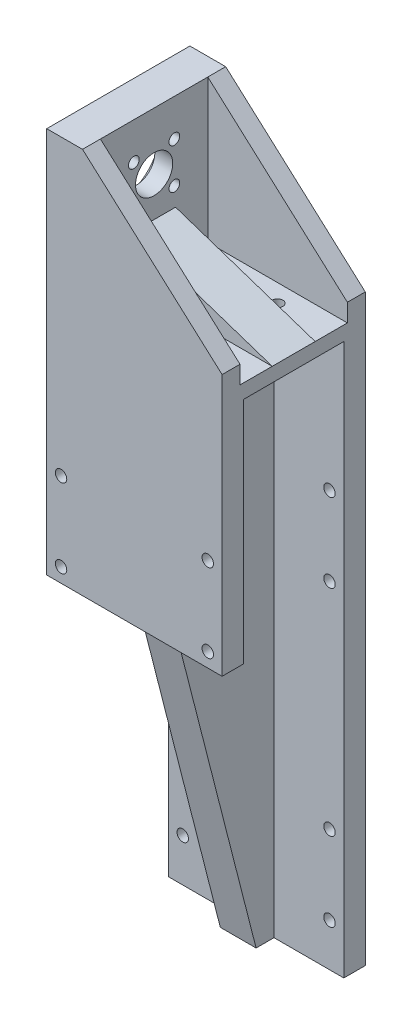
SolidWorks part; units mm, degrees
ref_plane "前视基准面" through (0, 0, 0) normal (0, 0, 1) x (1, 0, 0)
ref_plane "上视基准面" through (0, 0, 0) normal (0, 1, 0) x (1, 0, 0)
ref_plane "右视基准面" through (0, 0, 0) normal (1, 0, 0) x (0, 0, -1)
other "Configuration Table"
sketch "草图1" plane through (0, 0, 0) normal (0, 1, 0) x (1, 0, 0)
  line L1 (-24.5, -20) -> (24.5, -20)
  line L2 (-24.5, -20) -> (-24.5, 20)
  line L3 (-24.5, 20) -> (24.5, 20)
  line L4 (24.5, -20) -> (24.5, 20)
  line L5 (-24.5, -20) -> (24.5, 20) construction
  line L6 (-24.5, 20) -> (24.5, -20) construction
  point P0 (0, 0)
  dimension "D1" = 49
  dimension "D2" = 40
extrude "凸台-拉伸1" add sketch "草图1" along normal blind 4
sketch "草图2" plane through (0, 4, 0) normal (0, 1, 0) x (1, 0, 0)
  line L0 (0, 20) -> (0, -20) construction
  line L1 (24.5, 20) -> (-24.5, 20) construction
  line L2 (-24.5, -20) -> (24.5, -20) construction
  line L3 (-24.5, 0) -> (24.5, 0) construction
  line L4 (-24.5, 20) -> (-24.5, -20) construction
  line L5 (24.5, -20) -> (24.5, 20) construction
  circle A0 centre (-10, 10) radius 1.5
  circle A1 centre (10, 10) radius 1.5
  circle A2 centre (10, -10) radius 1.5
  circle A3 centre (-10, -10) radius 1.5
  dimension "D1" = 3
  dimension "D2" = 3
  dimension "D3" = 3
  dimension "D4" = 3
  dimension "D5" = 20
  dimension "D6" = 20
extrude "切除-拉伸1" cut sketch "草图2" against normal through all
sketch "草图3" plane through (0, 4, 0) normal (0, 1, 0) x (1, 0, 0)
  line L5 (-24.5, 0) -> (24.5, 0) construction
  line L6 (-24.5, 20) -> (-24.5, -20) construction
  line L7 (24.5, -20) -> (24.5, 20) construction
  line L9 (-24.5, 15) -> (-14.5, 15)
  line L10 (-24.5, 15) -> (-24.5, -15)
  line L11 (-24.5, -15) -> (-14.5, -15)
  line L12 (-14.5, 15) -> (-14.5, -15)
  dimension "D1" = 10
  dimension "D2" = 30
extrude "凸台-拉伸3" add sketch "草图3" along normal blind 40
sketch "草图4" plane through (-24.5, 0, 0) normal (-1, 0, 0) x (0, 0, 1)
  line L0 (0, 44) -> (0, 0) construction
  line L1 (-15, 44) -> (15, 44) construction
  line L2 (15, 4) -> (20, 4) construction
  circle A0 centre (0, 28) radius 5.2
  dimension "D1" = 10.4
  dimension "D2" = 24
extrude "切除-拉伸2" cut sketch "草图4" against normal through all
sketch "草图5" plane through (-24.5, 0, 0) normal (-1, 0, 0) x (0, 0, 1)
  circle A0 centre (0, 28) radius 11.75
  dimension "D1" = 23.5
extrude "切除-拉伸3" cut sketch "草图5" against normal blind 5
sketch "草图6" plane through (-19.5, 0, 0) normal (-1, 0, 0) x (0, 0, 1)
  line L1 (-5.6569, 22.3431) -> (5.6569, 22.3431) construction
  line L2 (-5.6569, 22.3431) -> (-5.6569, 33.6569) construction
  line L3 (-5.6569, 33.6569) -> (5.6569, 33.6569) construction
  line L4 (5.6569, 22.3431) -> (5.6569, 33.6569) construction
  line L5 (-5.6569, 22.3431) -> (5.6569, 33.6569) construction
  line L6 (-5.6569, 33.6569) -> (5.6569, 22.3431) construction
  circle A0 centre (0, 28) radius 8 construction
  circle A1 centre (-5.6569, 33.6569) radius 1.5
  circle A2 centre (5.6569, 33.6569) radius 1.5
  circle A3 centre (5.6569, 22.3431) radius 1.5
  circle A4 centre (-5.6569, 22.3431) radius 1.5
  dimension "D1" = 16
  dimension "D2" = 3
  dimension "D3" = 3
  dimension "D4" = 3
  dimension "D5" = 3
extrude "切除-拉伸4" cut sketch "草图6" against normal through all
ref_plane "基准面2" through (0, 0, 0) normal (0, 0, -1) x (-1, 0, 0)
sketch "草图7" plane through (0, 0, 0) normal (0, 0, -1) x (-1, 0, 0)
  line L0 (14.5, 17) -> (-24.5, 4)
  line L1 (14.5, 44) -> (14.5, 4) construction
  line L2 (-24.5, 4) -> (14.5, 4)
  line L3 (14.5, 4) -> (14.5, 17)
  dimension "D1" = 13
extrude "凸台-拉伸4" add sketch "草图7" along normal mid plane 12
sketch "草图8" plane through (-24.5, 0, 0) normal (-1, 0, 0) x (0, 0, 1)
  line L1 (20, 0) -> (14, 0)
  line L2 (20, 0) -> (20, -64)
  line L3 (20, -64) -> (14, -64)
  line L4 (14, 0) -> (14, -64)
  line L5 (-20, 0) -> (-14, 0)
  line L6 (-20, 0) -> (-20, -64)
  line L7 (-20, -64) -> (-14, -64)
  line L8 (-14, 0) -> (-14, -64)
  dimension "D1" = 6
  dimension "D2" = 6
  dimension "D3" = 64
  dimension "D4" = 64
extrude "凸台-拉伸5" add sketch "草图8" against normal up to surface (49 mm away) up to face at (24.5, 2.6667, 0)
sketch "草图9" plane through (0, 0, 20) normal (0, 0, 1) x (1, 0, 0)
  line L0 (24.5, 4) -> (24.5, -64) construction
  line L1 (24.5, -64) -> (-24.5, -64) construction
  line L2 (-24.5, 4) -> (-24.5, -64) construction
  circle A0 centre (20.5, -60) radius 1.6
  circle A1 centre (-20.5, -60) radius 1.6
  circle A2 centre (20.5, -38) radius 1.6
  circle A3 centre (-20.5, -38) radius 1.6
  dimension "D1" = 3.2
  dimension "D2" = 3.2
  dimension "D3" = 3.2
  dimension "D4" = 3.2
  dimension "D5" = 4
  dimension "D6" = 4
  dimension "D7" = 4
  dimension "D8" = 4
  dimension "D9" = 4
  dimension "D10" = 26
  dimension "D11" = 4
  dimension "D12" = 26
extrude "切除-拉伸5" cut sketch "草图9" against normal through all
sketch "草图11" plane through (0, 0, 15) normal (0, 0, 1) x (1, 0, 0)
  line L0 (-14.5, 44) -> (24.5, 9)
  line L1 (-24.5, 4) -> (-14.5, 4)
  line L2 (-24.5, 4) -> (-24.5, 44)
  line L3 (-24.5, 44) -> (-14.5, 44)
  line L5 (24.5, 9) -> (24.5, 4)
  line L6 (24.5, 4) -> (-14.5, 4)
  dimension "D1" = 5
extrude "凸台-拉伸6" add sketch "草图11" along normal blind 5
mirror "镜向2" about plane through (0, 0, 0) normal (0, 0, -1) of "凸台-拉伸6"
sketch "草图12" plane through (0, -64, 0) normal (0, -1, 0) x (1, 0, 0)
  line L1 (-24.5, -14) -> (24.5, -14)
  line L2 (-24.5, -14) -> (-24.5, -20)
  line L3 (-24.5, -20) -> (24.5, -20)
  line L4 (24.5, -14) -> (24.5, -20)
extrude "凸台-拉伸7" add sketch "草图12" along normal blind 90
sketch "草图13" plane through (0, 0, -20) normal (0, 0, -1) x (-1, 0, 0)
  line L0 (-20.5, -38) -> (-20.5, -149.0195) construction
  line L1 (20.5, -38) -> (20.5, -149.0195) construction
  line L2 (-20.5, -120) -> (20.5, -120) construction
  line L3 (-20.5, -142) -> (20.5, -142) construction
  circle A2 centre (-20.5, -120) radius 1.6
  circle A3 centre (-20.5, -142) radius 1.6
  circle A4 centre (20.5, -120) radius 1.6
  circle A5 centre (20.5, -142) radius 1.6
  point P16 (-20.5, -60)
  dimension "D1" = 3.2
  dimension "D6" = 82
  dimension "D3" = 22
extrude "切除-拉伸6" cut sketch "草图13" against normal through all
ref_plane "基准面3" through (0, 0, 0) normal (1, 0, 0) x (0, 0, -1)
sketch "草图14" plane through (0, 0, 0) normal (1, 0, 0) x (0, 0, -1)
  line L1 (14, 0) -> (-14, 0)
  line L2 (14, 0) -> (14, -64)
  line L4 (-14, 0) -> (-14, -64)
  line L5 (14, -154) -> (14, -64)
  line L6 (14, -154) -> (9, -154)
  line L7 (9, -154) -> (-14, -64)
  dimension "D1" = 5
extrude "凸台-拉伸8" add sketch "草图14" along normal mid plane 10
